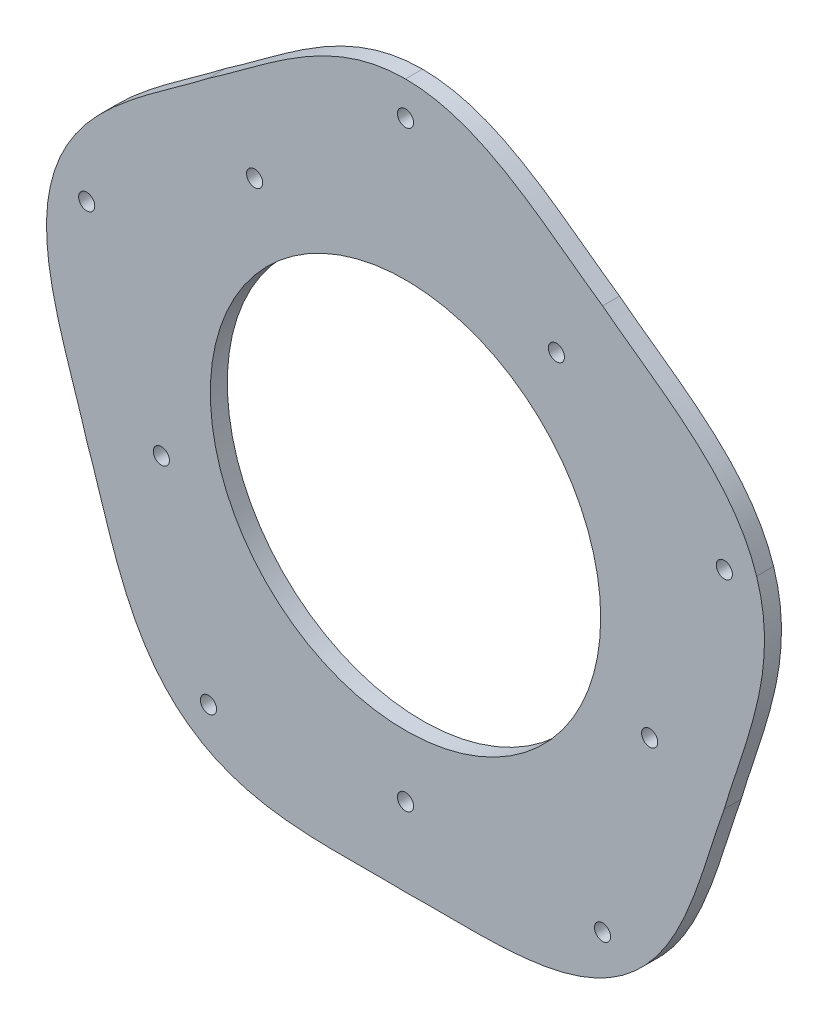
SolidWorks part; units mm, degrees
material "ABS"
ref_plane "Płaszczyzna przednia" through (0, 0, 0) normal (0, 0, 1) x (1, 0, 0)
ref_plane "Płaszczyzna górna" through (0, 0, 0) normal (0, 1, 0) x (1, 0, 0)
ref_plane "Płaszczyzna prawa" through (0, 0, 0) normal (1, 0, 0) x (0, 0, -1)
sketch "Szkic1" plane through (0, 0, 0) normal (0, 0, 1) x (1, 0, 0)
  line L0 (0, 0) -> (51.1373, 70.3845) construction
  line L1 (0, 0) -> (0, 87) construction
  circle A0 centre (0, 0) radius 79 construction
  circle A5 centre (0, 79) radius 1.9
  circle A9 centre (75.1335, 24.4123) radius 1.9
  circle A10 centre (46.435, -63.9123) radius 1.9
  circle A11 centre (-46.435, -63.9123) radius 1.9
  circle A12 centre (-75.1335, 24.4123) radius 1.9
  circle A13 centre (0, 0) radius 87 construction
  circle A54 centre (0, 0) radius 72.5
  circle A55 centre (0, 0) radius 46
  circle A56 centre (0, 0) radius 52
  circle A57 centre (0, 0) radius 68.5
  circle A59 centre (35.561, 48.9455) radius 1.9
  circle A60 centre (0, 0) radius 60.5 construction
  circle A64 centre (57.5389, -18.6955) radius 1.9
  circle A65 centre (0, -60.5) radius 1.9
  circle A66 centre (-57.5389, -18.6955) radius 1.9
  circle A67 centre (-35.561, 48.9455) radius 1.9
  spline S0 degree 3 poles (0, 87) (18.2248, 86.9986) (32.2889, 73.5369) (46.435, 63.9123) knots 0 0 0 0 1 1 1 1
  spline S1 degree 3 poles (82.7419, 26.8845) (77.1088, 44.2169) (59.9599, 53.4327) (46.435, 63.9123) knots 0 0 0 0 1 1 1 1
  spline S2 degree 3 poles (82.7419, 26.8845) (88.3724, 9.5512) (79.9156, -7.9844) (75.1335, -24.4123) knots 0 0 0 0 1 1 1 1
  spline S3 degree 3 poles (51.1373, -70.3845) (65.8807, -59.6711) (69.3462, -40.5137) (75.1335, -24.4123) knots 0 0 0 0 1 1 1 1
  spline S4 degree 3 poles (51.1373, -70.3845) (36.3923, -81.0957) (17.1016, -78.4715) (0, -79) knots 0 0 0 0 1 1 1 1
  spline S5 degree 3 poles (-51.1373, -70.3845) (-36.3923, -81.0957) (-17.1016, -78.4715) (0, -79) knots 0 0 0 0 1 1 1 1
  spline S6 degree 3 poles (-51.1373, -70.3845) (-65.8807, -59.6711) (-69.3462, -40.5137) (-75.1335, -24.4123) knots 0 0 0 0 1 1 1 1
  spline S7 degree 3 poles (-82.7419, 26.8845) (-88.3724, 9.5512) (-79.9156, -7.9844) (-75.1335, -24.4123) knots 0 0 0 0 1 1 1 1
  spline S8 degree 3 poles (-82.7419, 26.8845) (-77.1088, 44.2169) (-59.9599, 53.4327) (-46.435, 63.9123) knots 0 0 0 0 1 1 1 1
  spline S9 degree 3 poles (0, 87) (-18.2248, 86.9986) (-32.2889, 73.5369) (-46.435, 63.9123) knots 0 0 0 0 1 1 1 1
  point P18 (0, 0)
  point P27 (0, 0)
  point P64 (0, 0)
  point P69 (0, 0)
  point P188 (0, 0)
  dimension "D1" = 158
  dimension "D2" = 145
  dimension "D3" = 92
  dimension "D4" = 3.8
  dimension "D5" = 6
  dimension "D8" = 174
  dimension "D10" = 121
  dimension "D11" = 3.8
  dimension "D9" = 36
  dimension "D12" = 5
  dimension "D6" = 4
  dimension "D7" = 5
extrude "Dodanie-wyciągnięcie1" add sketch "Szkic1" along normal blind 4
